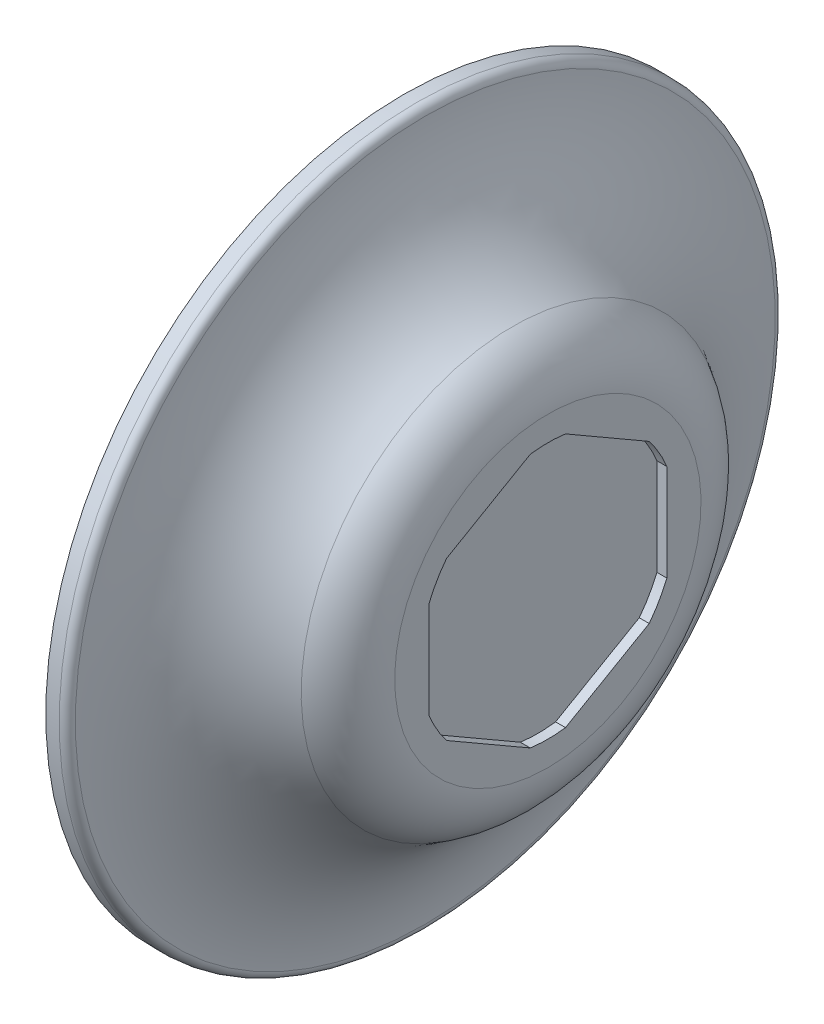
SolidWorks part; units mm, degrees
ref_plane "Front" through (0, 0, 0) normal (0, 0, 1) x (1, 0, 0)
ref_plane "Right" through (0, 0, 0) normal (0, 1, 0) x (1, 0, 0)
ref_plane "Top" through (0, 0, 0) normal (1, 0, 0) x (0, 0, -1)
sketch "Sketch1" plane through (0, 0, 0) normal (0, 0, 1) x (1, 0, 0)
  line L0 (6.9494, 0) -> (16.0499, 0) construction
  line L1 (6.9494, 0) -> (9.4132, 0)
  line L2 (9.4132, 0) -> (9.4132, 11.7436)
  line L3 (6.9494, 0) -> (6.9494, 15.598)
  line L4 (0, 27.432) -> (-1.651, 27.432)
  line L5 (-1.651, 27.432) -> (-1.651, 26.162)
  line L6 (-1.651, 26.162) -> (-0.3958, 26.162)
  arc A0 (9.4132, 11.7436) -> (6.7237, 16.226) centre (4.3332, 11.7436) ccw
  arc A1 (6.7237, 16.226) -> (0, 27.432) centre (12.7, 27.432) cw
  arc A3 (-0.3958, 26.162) -> (6.9494, 15.598) centre (12.7, 27.432) ccw
  dimension "D2" = 12.7
  dimension "D3" = 13.1572
  dimension "D8" = 5.08
  dimension "D1" = 27.432
  dimension "D4" = 1.651
  dimension "D5" = 1.27
  dimension "D6" = 2.4638
  dimension "D7" = 11.0642
revolve "Main Body" add sketch "Sketch1" angle 360 about L0
sketch "Sketch2" plane through (9.4132, 0, 0) normal (1, 0, 0) x (0, 0, -1)
  circle A0 centre (0, 0) radius 3.3655
  circle A1 centre (0, 0) radius 11.7436 construction
  dimension "D1" = 6.731
extrude "Center Hole" [suppressed] cut sketch "Sketch2" against normal through all
sketch "Sketch3" plane through (9.4132, 0, 0) normal (1, 0, 0) x (0, 0, -1)
  line L0 (-9.1186, 3.7049) -> (-9.1186, -3.7049)
  line L1 (0, 0) -> (0, 7.0824) construction
  line L2 (9.1186, 3.7049) -> (9.1186, -3.7049)
  line L3 (1.3508, -9.7494) -> (7.7678, -6.0445)
  line L4 (0, 0) -> (-5.7302, -3.3083) construction
  line L5 (1.3508, 9.7494) -> (7.7678, 6.0445)
  line L6 (0, 0) -> (5.099, -2.9439) construction
  line L7 (-7.7678, -6.0445) -> (-1.3508, -9.7494)
  line L8 (0, 0) -> (7.3956, 0) construction
  line L10 (-7.7678, 6.0445) -> (-1.3508, 9.7494)
  arc A0 (1.3508, 9.7494) -> (-1.3508, 9.7494) centre (0, 0) ccw
  arc A1 (9.1186, 3.7049) -> (7.7678, 6.0445) centre (0, 0) ccw
  arc A2 (7.7678, -6.0445) -> (9.1186, -3.7049) centre (0, 0) ccw
  arc A3 (-1.3508, -9.7494) -> (1.3508, -9.7494) centre (0, 0) ccw
  arc A4 (-9.1186, -3.7049) -> (-7.7678, -6.0445) centre (0, 0) ccw
  arc A5 (-7.7678, 6.0445) -> (-9.1186, 3.7049) centre (0, 0) ccw
  circle A6 centre (0, 0) radius 27.432 construction
  dimension "D1" = 19.685
  dimension "D2" = 18.2372
  dimension "D5" = 120
  dimension "D6" = 120
extrude "Hex" cut sketch "Sketch3" against normal blind 0.762
sketch "Sketch4" plane through (6.9494, 0, 0) normal (-1, 0, 0) x (0, 0, 1)
  circle A0 centre (0, 0) radius 12.2555
  circle A1 centre (0, 0) radius 15.598 construction
  dimension "D1" = 24.511
extrude "Back Recess" cut sketch "Sketch4" against normal blind 0.7493
fillet "Fillet1" radius 0.635 1 edges at (0, -27.432, 0)
